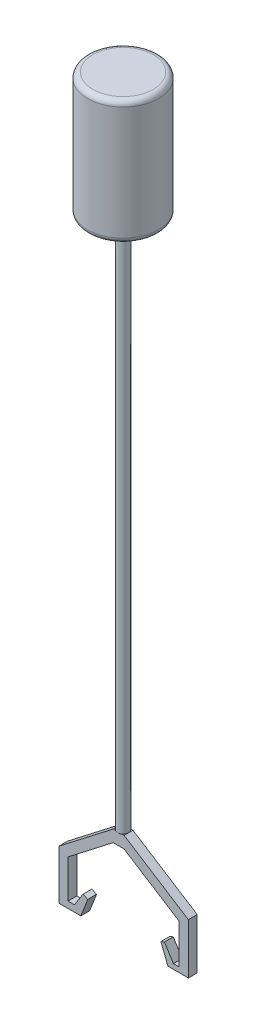
SolidWorks part; units mm, degrees
ref_plane "Alzado" through (0, 0, 0) normal (0, 0, 1) x (1, 0, 0)
ref_plane "Planta" through (0, 0, 0) normal (0, 1, 0) x (1, 0, 0)
ref_plane "Vista lateral" through (0, 0, 0) normal (1, 0, 0) x (0, 0, -1)
sketch "Croquis1" plane through (0, 0, 0) normal (0, 1, 0) x (1, 0, 0)
  circle A0 centre (0, 0) radius 100
  dimension "D1" = 200
extrude "Saliente-Extruir1" add sketch "Croquis1" along normal blind 350
fillet "Redondeo1" radius 15 2 edges at (0, 0, 100) (0, 350, 100)
sketch "Croquis2" plane through (0, 0, 0) normal (0, -1, 0) x (1, 0, 0)
  circle A0 centre (0, 0) radius 15.3747
extrude "Saliente-Extruir2" add sketch "Croquis2" along normal blind 1500
sketch "Croquis3" plane through (0, 0, 0) normal (0, 0, 1) x (1, 0, 0)
  line L0 (15.3747, -1500) -> (196.6433, -1615.2477)
  line L1 (196.6433, -1615.2477) -> (196.6433, -1757.6089)
  line L2 (196.6433, -1757.6089) -> (169.8909, -1757.6089)
  line L3 (169.8909, -1743.6573) -> (169.8909, -1631.4903)
  line L4 (169.8909, -1631.4903) -> (15.3747, -1533.2513)
  line L5 (15.3747, -1533.2513) -> (-15.3747, -1533.2513)
  line L6 (-15.3747, -1533.2513) -> (-142.5394, -1631.4903)
  line L7 (-142.5394, -1631.4903) -> (-142.5394, -1739.3898)
  line L8 (-15.3747, -1500) -> (-158.6263, -1610.6667)
  line L9 (-158.6263, -1610.6667) -> (-168.7998, -1618.526)
  line L10 (-168.7998, -1618.526) -> (-168.7998, -1757.6089)
  line L11 (-168.7998, -1757.6089) -> (-142.5394, -1757.6089)
  line L12 (15.3747, -1500) -> (-15.3747, -1500)
  line L13 (169.8909, -1757.6089) -> (138.993, -1757.6089)
  line L14 (138.993, -1757.6089) -> (119.1053, -1707.328)
  line L15 (119.1053, -1707.328) -> (129.0492, -1703.3949)
  line L16 (129.0492, -1703.3949) -> (154.4419, -1743.6573)
  line L17 (154.4419, -1743.6573) -> (169.8909, -1743.6573)
  line L18 (-142.5394, -1757.6089) -> (-106.6095, -1757.6089)
  line L19 (-106.6095, -1757.6089) -> (-87.0005, -1707.328)
  line L20 (-87.0005, -1707.328) -> (-100.7748, -1701.9562)
  line L21 (-100.7748, -1701.9562) -> (-120.174, -1732.4684)
  line L22 (-120.174, -1732.4684) -> (-124.5745, -1739.3898)
  line L23 (-124.5745, -1739.3898) -> (-142.5394, -1739.3898)
extrude "Saliente-Extruir3" add sketch "Croquis3" along normal mid plane 25
